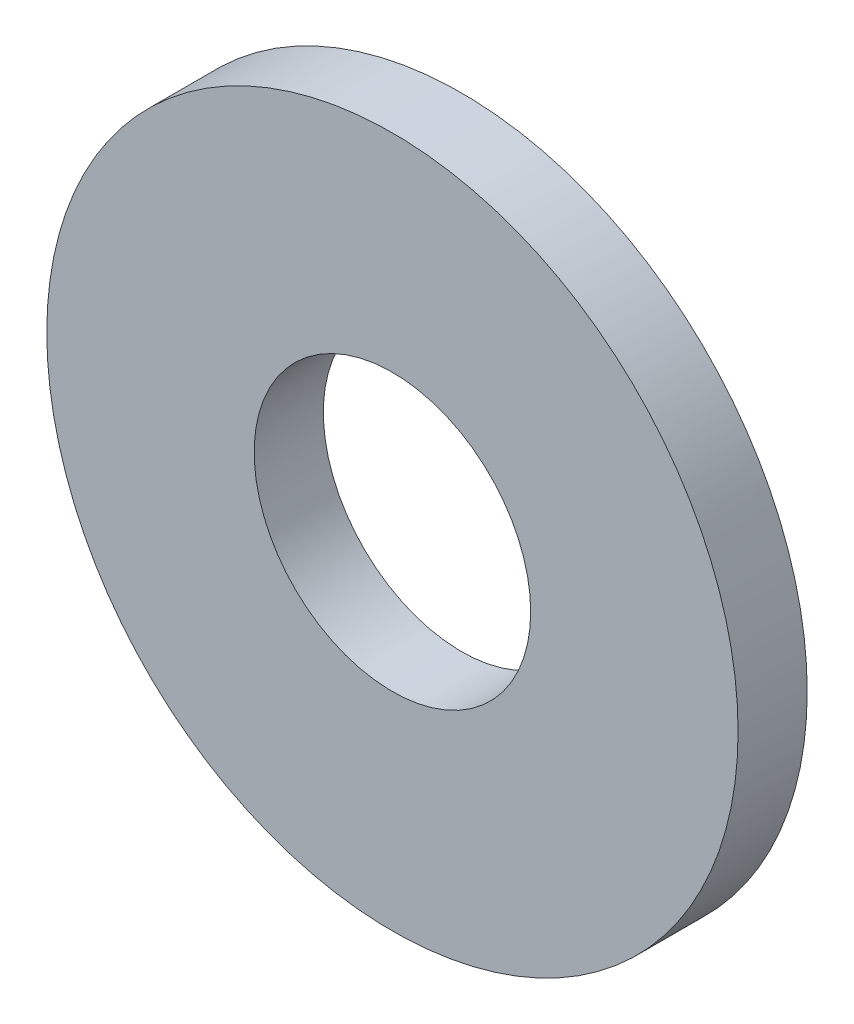
SolidWorks part; units mm, degrees
ref_plane "Front Plane" through (0, 0, 0) normal (0, 0, 1) x (1, 0, 0)
ref_plane "Top Plane" through (0, 0, 0) normal (0, 1, 0) x (1, 0, 0)
ref_plane "Right Plane" through (0, 0, 0) normal (1, 0, 0) x (0, 0, -1)
sketch "Sketch1" plane through (0, 0, 0) normal (0, 0, 1) x (1, 0, 0)
  circle A0 centre (0, 0) radius 7.9375
  circle A1 centre (0, 0) radius 3.175
  dimension "D1" = 15.875
  dimension "ID" = 6.35
extrude "Extrude1" add sketch "Sketch1" along normal mid plane 1.5875
sketch "Sketch2" plane through (0, 0, 0) normal (1, 0, 0) x (0, 0, -1)
  line L0 (-0.7937, -3.175) -> (0.7937, -3.175) construction
  line L3 (0.7937, 3.175) -> (-0.7937, 3.175) construction
  line L5 (-0.7937, -3.175) -> (0.7937, -3.175)
  line L6 (0.7937, 3.175) -> (-0.7937, 3.175)
sketch "Sketch4" plane through (0, 0, 0.7937) normal (0, 0, 1) x (1, 0, 0)
  line L0 (0, 0) -> (-2.2451, 2.2451)
  line L1 (0, -2.6194) -> (0, 2.6194) construction
  circle A0 centre (0, 0) radius 3.175 construction
  dimension "D1" = 45
